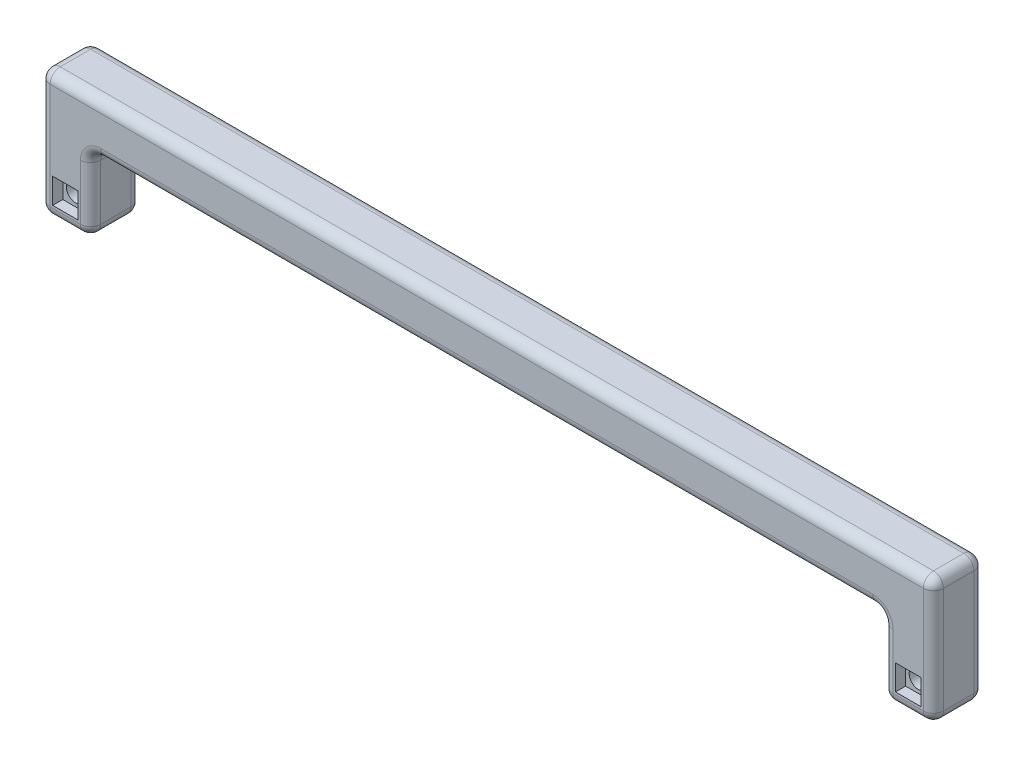
SolidWorks part; units mm, degrees
ref_plane "Front Plane" through (0, 0, 0) normal (0, 0, 1) x (1, 0, 0)
ref_plane "Top Plane" through (0, 0, 0) normal (0, 1, 0) x (1, 0, 0)
ref_plane "Right Plane" through (0, 0, 0) normal (1, 0, 0) x (0, 0, -1)
sketch "Sketch1" plane through (0, 0, 0) normal (0, 0, 1) x (1, 0, 0)
  line L1 (0, 0) -> (224.4725, 0)
  line L2 (0, 0) -> (0, 12.7)
  line L3 (0, 12.7) -> (224.4725, 12.7)
  line L4 (224.4725, 0) -> (224.4725, 12.7)
  dimension "D1" = 224.4725
  dimension "D2" = 12.7
extrude "Boss-Extrude1" add sketch "Sketch1" along normal blind 12.7
ref_plane "Plane1" through (112.2362, 0, 0) normal (-1, 0, 0) x (0, 0, 1)
sketch "Sketch2" plane through (0, 0, 0) normal (0, -1, 0) x (1, 0, 0)
  line L0 (0, 12.7) -> (224.4725, 12.7) construction
  line L1 (0, 0) -> (12.7, 0)
  line L2 (0, 0) -> (0, 12.7)
  line L3 (0, 12.7) -> (12.7, 12.7)
  line L4 (12.7, 0) -> (12.7, 12.7)
  dimension "D1" = 12.7
extrude "Boss-Extrude2" add sketch "Sketch2" along normal blind 19.05
sketch "Sketch3" plane through (0, 0, 12.7) normal (0, 0, 1) x (1, 0, 0)
  line L0 (12.7, -19.05) -> (0, -19.05) construction
  line L1 (0, 12.7) -> (0, -19.05) construction
  circle A0 centre (6.35, -12.7) radius 2.286
  dimension "D3" = 4.572
  dimension "D1" = 6.35
  dimension "D2" = 6.35
extrude "Cut-Extrude1" cut sketch "Sketch3" against normal through all
sketch "Sketch4" plane through (0, 0, 12.7) normal (0, 0, 1) x (1, 0, 0)
  line L1 (3.175, -9.525) -> (9.525, -9.525)
  line L2 (3.175, -9.525) -> (3.175, -15.875)
  line L3 (3.175, -15.875) -> (9.525, -15.875)
  line L4 (9.525, -9.525) -> (9.525, -15.875)
  line L5 (3.175, -9.525) -> (9.525, -15.875) construction
  line L6 (3.175, -15.875) -> (9.525, -9.525) construction
  point P0 (6.35, -12.7)
  dimension "D1" = 6.35
  dimension "D2" = 6.35
extrude "Cut-Extrude2" cut sketch "Sketch4" against normal blind 2.54
mirror "Mirror1" about plane through (112.2362, 0, 0) normal (-1, 0, 0) of "Cut-Extrude2", "Cut-Extrude1", "Boss-Extrude2"
fillet "Fillet1" radius 2.54 24 edges at (12.7, -9.525, 0) (12.7, -9.525, 12.7) (211.7725, -9.525, 0) (211.7725, -9.525, 12.7) (6.35, -19.05, 12.7) (12.7, -19.05, 6.35) (6.35, -19.05, 0) (0, -3.175, 12.7) (0, -19.05, 6.35) (0, -3.175, 0) (218.1225, -19.05, 12.7) (218.1225, -19.05, 0) (211.7725, -19.05, 6.35) (12.7, 0, 6.35) (112.2362, 0, 12.7) (211.7725, 0, 6.35) (112.2362, 0, 0) (224.4725, -19.05, 6.35) (224.4725, -3.175, 12.7) (224.4725, -3.175, 0) (224.4725, 12.7, 6.35) (112.2362, 12.7, 12.7) (0, 12.7, 6.35) (112.2362, 12.7, 0)
